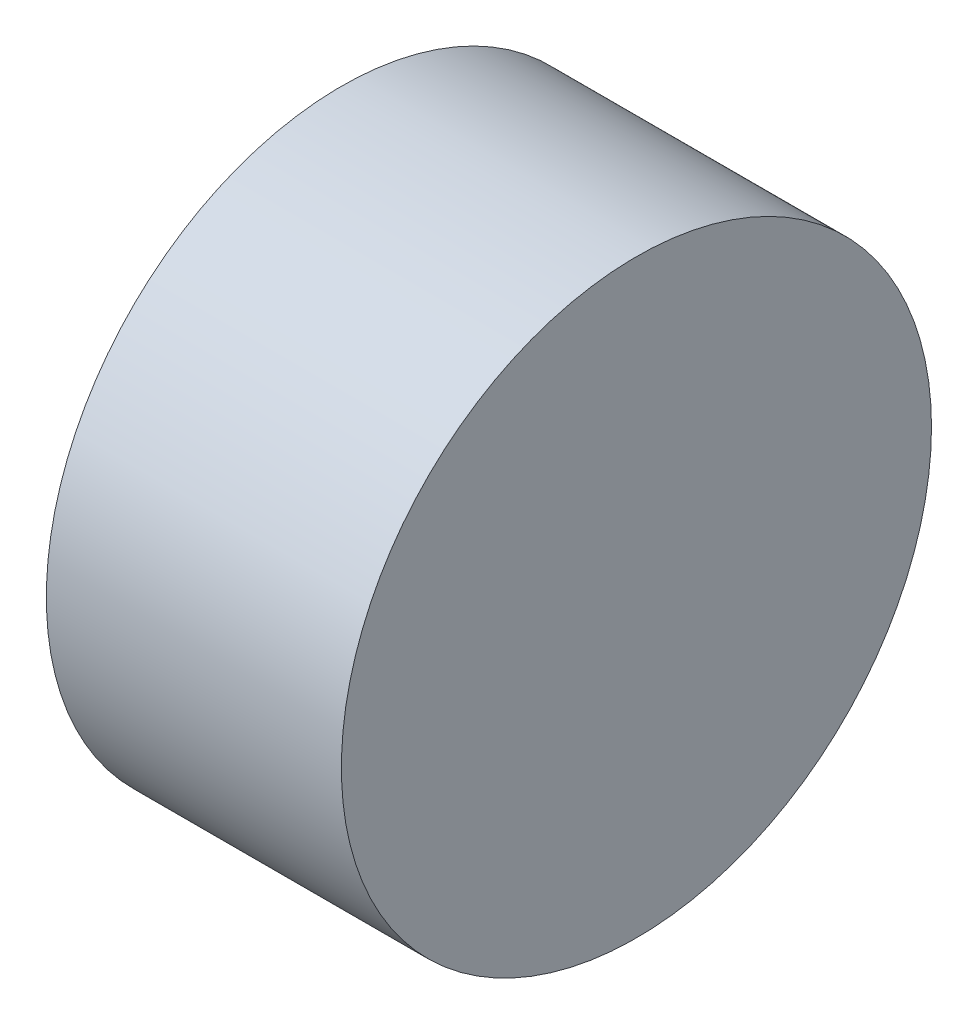
SolidWorks part; units mm, degrees
ref_plane "Front Plane" through (0, 0, 0) normal (0, 0, 1) x (1, 0, 0)
ref_plane "Top Plane" through (0, 0, 0) normal (0, 1, 0) x (1, 0, 0)
ref_plane "Right Plane" through (0, 0, 0) normal (1, 0, 0) x (0, 0, -1)
sketch "Sketch1" plane through (0, 0, 0) normal (1, 0, 0) x (0, 0, -1)
  circle A0 centre (0, 0) radius 30
  dimension "D1" = 60
extrude "Boss-Extrude1" add sketch "Sketch1" along normal blind 30
sketch "Sketch2" plane through (0, 0, 0) normal (-1, 0, 0) x (0, 0, 1)
  line L1 (3.0507, -2.1355) -> (3.3748, 1.5743)
  line L2 (3.3748, 1.5743) -> (0.324, 3.7098)
  line L3 (0.324, 3.7098) -> (-3.0507, 2.1355)
  line L4 (-3.0507, 2.1355) -> (-3.3748, -1.5743)
  line L5 (-3.3748, -1.5743) -> (-0.324, -3.7098)
  line L6 (-0.324, -3.7098) -> (3.0507, -2.1355)
  circle A0 centre (0, 0) radius 3.225 construction
  dimension "D1" = 6.45
extrude "Cut-Extrude1" cut sketch "Sketch2" against normal blind 10
